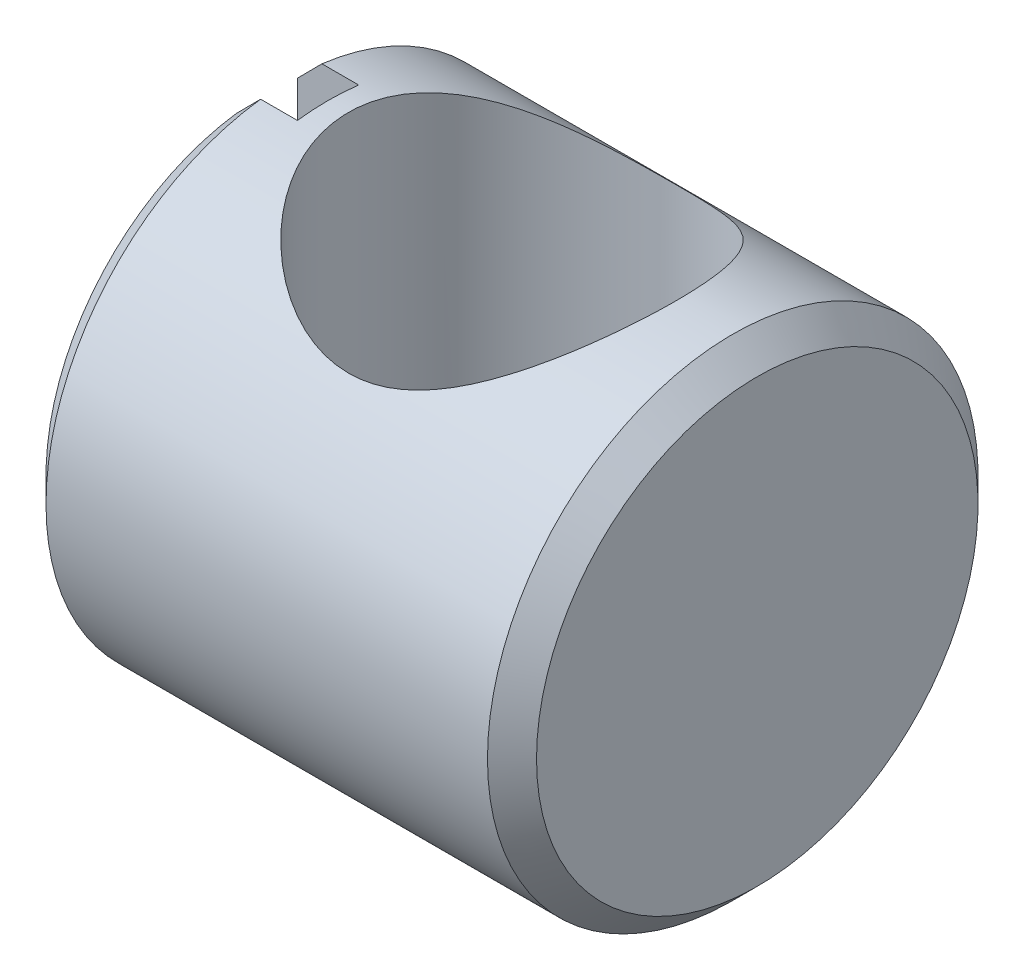
SolidWorks part; units mm, degrees
material "Plain Carbon Steel"
ref_plane "Front Plane" through (0, 0, 0) normal (0, 0, 1) x (1, 0, 0)
ref_plane "Top Plane" through (0, 0, 0) normal (0, 1, 0) x (1, 0, 0)
ref_plane "Right Plane" through (0, 0, 0) normal (1, 0, 0) x (0, 0, -1)
sketch "Sketch1" plane through (0, 0, 0) normal (1, 0, 0) x (0, 0, -1)
  circle A0 centre (0, 0) radius 6
  dimension "D1" = 12
extrude "Boss-Extrude1" add sketch "Sketch1" along normal mid plane 12
chamfer "Chamfer1" distance 0.6 angle 45 2 edges at (-6, 0, -6) (6, 0, -6)
sketch "Sketch2" plane through (0, 0, 0) normal (0, 1, 0) x (1, 0, 0)
  circle A0 centre (0, 0) radius 4
  dimension "D1" = 8
extrude "Cut-Extrude1" cut sketch "Sketch2" against normal through all both and the other way through all
sketch "Sketch3" plane through (-6, 0, 0) normal (-1, 0, 0) x (0, 0, 1)
  line L0 (-0.75, -6.9133) -> (-0.75, 6.9133)
  line L1 (-0.75, -6.9133) -> (0.75, -6.9133)
  line L2 (-0.75, 6.9133) -> (0.75, 6.9133)
  line L3 (0.75, -6.9133) -> (0.75, 6.9133)
  line L4 (-0.75, -6.9133) -> (0.75, 6.9133) construction
  line L5 (-0.75, 6.9133) -> (0.75, -6.9133) construction
  point P1 (0, 0)
  dimension "D1" = 1.5
extrude "Cut-Extrude2" cut sketch "Sketch3" against normal blind 1.5
